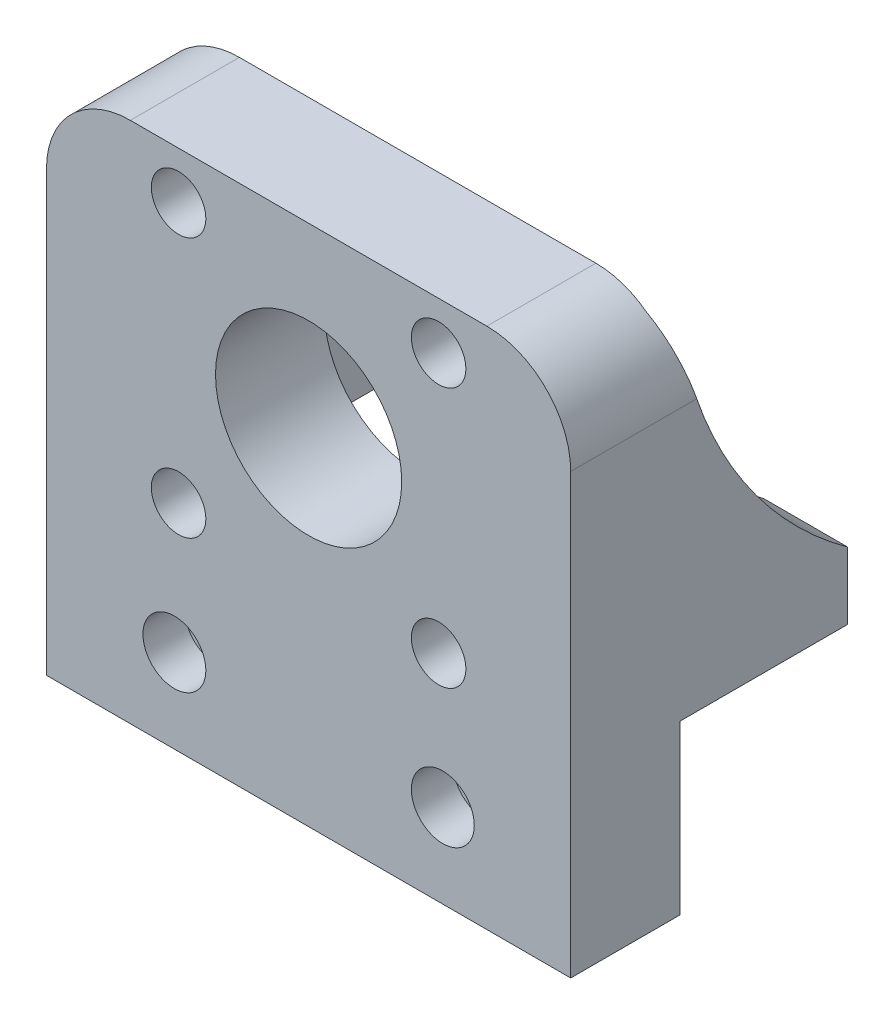
SolidWorks part; units mm, degrees
ref_plane "Alzado" through (0, 0, 0) normal (0, 0, 1) x (1, 0, 0)
ref_plane "Planta" through (0, 0, 0) normal (0, 1, 0) x (1, 0, 0)
ref_plane "Vista lateral" through (0, 0, 0) normal (1, 0, 0) x (0, 0, -1)
sketch "Croquis1" plane through (0, 0, 0) normal (0, 0, 1) x (1, 0, 0)
  line L0 (255, -10) -> (0, -10) construction
  line L1 (96.25, -10) -> (158.75, -10)
  line L2 (96.25, -10) -> (96.25, 52.3)
  line L3 (96.25, 52.3) -> (158.75, 52.3)
  line L4 (158.75, -10) -> (158.75, 52.3)
  line L5 (144.65, 52.3) -> (110.35, 52.3) construction
  line L6 (127.5, 52.3) -> (127.5, 31.15) construction
  line L7 (106.25, 52.3) -> (106.25, -10) construction
  line L9 (148.75, 52.3) -> (148.75, -10) construction
  circle A0 centre (127.5, 31.15) radius 11.1
  circle A1 centre (112, 46.65) radius 1.55
  circle A2 centre (143, 46.65) radius 1.55
  circle A3 centre (143, 15.65) radius 1.55
  circle A4 centre (112, 15.65) radius 1.55
  circle A5 centre (111.5, 0) radius 2.05
  circle A6 centre (143.5, 0) radius 2.05
  dimension "D1" = 22.2
  dimension "D5" = 3.1
  dimension "D6" = 4.1
  dimension "D2" = 10
  dimension "D3" = 10
  dimension "D4" = 42.5
  dimension "D7" = 10
  dimension "D8" = 16
extrude "Saliente-Extruir1" add sketch "Croquis1" along normal blind 13
sketch "Croquis2" plane through (0, 0, 13) normal (0, 0, 1) x (1, 0, 0)
  circle A0 centre (112, 46.65) radius 3.25
  circle A1 centre (143, 46.65) radius 3.25
  circle A2 centre (143, 15.65) radius 3.25
  circle A3 centre (112, 15.65) radius 3.25
  circle A4 centre (111.5, 0) radius 3.75
  circle A5 centre (143.5, 0) radius 3.75
  dimension "D1" = 6.5
  dimension "D2" = 7.5
extrude "Cortar-Extruir1" cut sketch "Croquis2" against normal blind 5
sketch "Croquis4" plane through (158.75, 0, 0) normal (1, 0, 0) x (0, 0, -1)
  line L0 (0, -10) -> (0, 10) construction
  line L1 (0, 10) -> (20, 10) construction
  line L2 (20, 10) -> (20, -10) construction
  line L3 (20, -10) -> (0, -10) construction
  line L7 (0, 10) -> (20, 10)
  line L8 (20, 10) -> (20, 18)
  line L10 (0, 50.2908) -> (0, 10)
  arc A2 (0, 50.2908) -> (20, 18) centre (49.3215, 58.5) ccw
  dimension "D2" = 8
  dimension "D3" = 100
  dimension "D1" = 20
  dimension "D4" = 48.5
extrude "Saliente-Extruir2" add sketch "Croquis4" against normal blind 10
sketch "Croquis5" plane through (96.25, 0, 0) normal (-1, 0, 0) x (0, 0, 1)
  line L3 (0, 10) -> (0, 50.2908)
  line L4 (-20, 18) -> (-20, 10)
  line L5 (-20, 10) -> (0, 10)
  line L6 (0, 10) -> (0, 50.2908)
  line L7 (-20, 18) -> (-20, 10)
  line L8 (-20, 10) -> (0, 10)
  arc A1 (-20, 18) -> (0, 50.2908) centre (-49.3215, 58.5) ccw
  arc A2 (-20, 18) -> (0, 50.2908) centre (-49.3215, 58.5) ccw
  dimension "D1" = 0
extrude "Saliente-Extruir3" add sketch "Croquis5" against normal blind 10
sketch "Croquis6" plane through (0, 10, 0) normal (0, -1, 0) x (1, 0, 0)
  line L0 (148.75, 0) -> (158.75, 0) construction
  line L1 (153.75, 0) -> (153.75, -10) construction
  line L2 (127.5, 0) -> (127.5, -20.3637) construction
  line L3 (96.25, 0) -> (158.75, 0) construction
  circle A0 centre (101.25, -10) radius 2.05
  circle A1 centre (153.75, -10) radius 2.05
  dimension "D1" = 4.1
  dimension "D2" = 10
extrude "Cortar-Extruir2" cut sketch "Croquis6" against normal up to next
sketch "Croquis7" plane through (0, 10, 0) normal (0, -1, 0) x (1, 0, 0)
  circle A0 centre (101.25, -10) radius 3.75
  circle A1 centre (153.75, -10) radius 3.75
  dimension "D1" = 7.5
extrude "Cortar-Extruir3" cut sketch "Croquis7" against normal up to next from offset 10 offset against normal yes
fillet "Redondeo1" radius 10 2 edges at (96.25, 52.3, 6.5) (158.75, 52.3, 6.5)
